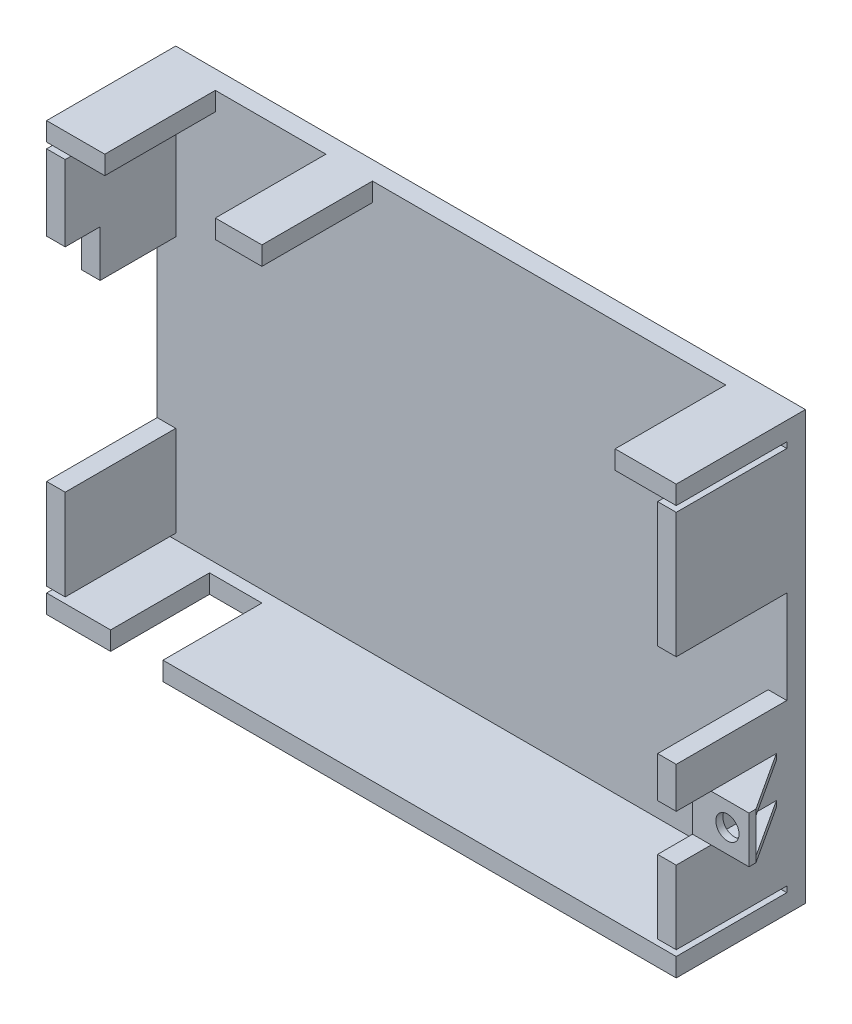
SolidWorks part; units mm, degrees
ref_plane "Front Plane" through (0, 0, 0) normal (0, 0, 1) x (1, 0, 0)
ref_plane "Top Plane" through (0, 0, 0) normal (0, 1, 0) x (1, 0, 0)
ref_plane "Right Plane" through (0, 0, 0) normal (1, 0, 0) x (0, 0, -1)
sketch "Sketch1" plane through (0, 0, 0) normal (0, 0, 1) x (1, 0, 0)
  line L1 (0, 0) -> (108.2, 0)
  line L2 (0, 0) -> (0, 73.5)
  line L3 (0, 73.5) -> (108.2, 73.5)
  line L4 (108.2, 0) -> (108.2, 73.5)
  dimension "D1" = 73.5
  dimension "D2" = 108.2
extrude "Boss-Extrude2" add sketch "Sketch1" along normal blind 3.2
sketch "Sketch2" plane through (0, 0, 3.2) normal (0, 0, 1) x (1, 0, 0)
  line L1 (3.2, 3.2) -> (105, 3.2)
  line L2 (3.2, 3.2) -> (3.2, 70.3)
  line L3 (3.2, 70.3) -> (105, 70.3)
  line L4 (0, 73.5) -> (0, 0)
  line L5 (0, 0) -> (108.2, 0)
  line L6 (108.2, 0) -> (108.2, 73.5)
  line L7 (108.2, 73.5) -> (0, 73.5)
  line L8 (0, 73.5) -> (0, 0)
  line L9 (0, 0) -> (108.2, 0)
  line L10 (108.2, 0) -> (108.2, 73.5)
  line L11 (108.2, 73.5) -> (0, 73.5)
  line L12 (105, 3.2) -> (105, 70.3)
  dimension "D2" = 3.2
  dimension "D3" = 3.2
  dimension "D4" = 3.2
  dimension "D5" = 3.2
  dimension "D1" = 0
extrude "Boss-Extrude3" add sketch "Sketch2" along normal blind 19
sketch "Sketch3" plane through (0, 0, 22.2) normal (0, 0, 1) x (1, 0, 0)
  line L0 (3.2, 70.3) -> (0, 70.3)
  line L1 (0, 70.3) -> (0, 69.3)
  line L2 (0, 69.3) -> (3.2, 69.3)
  line L3 (3.2, 70.3) -> (3.2, 3.2) construction
  line L4 (108.2, 73.5) -> (0, 73.5)
  line L5 (0, 73.5) -> (0, 0)
  line L6 (0, 0) -> (108.2, 0)
  line L7 (108.2, 0) -> (108.2, 73.5)
  line L9 (0, 70.3) -> (0, 69.3)
  line L11 (108.2, 3.2) -> (108.2, 4.2)
  line L12 (3.2, 69.3) -> (3.2, 70.3)
  line L13 (105, 70.3) -> (108.2, 70.3)
  line L14 (108.2, 70.3) -> (108.2, 69.3)
  line L15 (108.2, 69.3) -> (105, 69.3)
  line L16 (105, 3.2) -> (105, 70.3) construction
  line L17 (105, 69.3) -> (105, 70.3)
  line L18 (105, 3.2) -> (108.2, 3.2)
  line L19 (108.2, 3.2) -> (108.2, 4.2)
  line L20 (108.2, 4.2) -> (105, 4.2)
  line L21 (105, 4.2) -> (105, 3.2)
  line L22 (3.2, 3.2) -> (0, 3.2)
  line L23 (0, 3.2) -> (0, 4.2)
  line L24 (0, 4.2) -> (3.2, 4.2)
  line L25 (3.2, 4.2) -> (3.2, 3.2)
  line L26 (0, 4.2) -> (0, 0)
  line L27 (108.2, 69.3) -> (108.2, 70.3)
  line M10 (0, 73.5) -> (0, 0)
  line M12 (108.2, 0) -> (108.2, 73.5)
  line M14 (3.2, 3.2) -> (3.2, 70.3)
  line M16 (105, 70.3) -> (105, 3.2)
  dimension "D1" = 0
  dimension "D2" = 1
  dimension "D3" = 1
  dimension "D4" = 1
  dimension "D5" = 1
extrude "Cut-Extrude1" cut sketch "Sketch3" against normal blind 19 contours L2 L0 M10 M14 | L15 L13 M12 M16 | L20 L18 M12 M16 | L24 L25 L22 L23
sketch "Sketch4" plane through (0, 0, 22.2) normal (0, 0, 1) x (1, 0, 0)
  line L0 (0, 48.3) -> (3.2, 48.3)
  line L1 (0, 19.8) -> (3.2, 19.8)
  line L4 (0, 69.3) -> (0, 4.2)
  line L5 (0, 4.2) -> (3.2, 4.2)
  line L6 (3.2, 4.2) -> (3.2, 69.3)
  line L7 (3.2, 69.3) -> (0, 69.3)
  line L8 (0, 48.3) -> (0, 19.8)
  line L9 (0, 4.2) -> (3.2, 4.2) construction
  line L10 (3.2, 19.8) -> (3.2, 48.3)
  line L11 (3.2, 69.3) -> (0, 69.3) construction
  point P8 (1.6, 4.2)
  dimension "D2" = 21
  dimension "D3" = 15.6
  dimension "D1" = 0
extrude "Cut-Extrude2" cut sketch "Sketch4" against normal blind 19
sketch "Sketch5" plane through (0, 0, 22.2) normal (0, 0, 1) x (1, 0, 0)
  line L0 (10, 73.5) -> (10, 70.3)
  line L1 (29, 73.5) -> (29, 70.3)
  line L2 (37, 73.5) -> (37, 70.3)
  line L3 (97.7, 73.5) -> (97.7, 70.3)
  line L4 (0, 70.3) -> (108.2, 70.3)
  line L5 (108.2, 70.3) -> (108.2, 73.5)
  line L6 (108.2, 73.5) -> (0, 73.5)
  line L7 (0, 73.5) -> (0, 70.3)
  line L8 (10, 70.3) -> (29, 70.3)
  line L9 (108.2, 70.3) -> (108.2, 73.5) construction
  line L10 (97.7, 73.5) -> (37, 73.5)
  line L11 (0, 73.5) -> (0, 70.3) construction
  line L12 (29, 73.5) -> (10, 73.5)
  line L13 (37, 70.3) -> (97.7, 70.3)
  dimension "D2" = 10
  dimension "D3" = 19
  dimension "D4" = 8
  dimension "D5" = 10.5
  dimension "D1" = 0
extrude "Cut-Extrude3" cut sketch "Sketch5" against normal blind 19
sketch "Sketch6" plane through (0, 0, 22.2) normal (0, 0, 1) x (1, 0, 0)
  line L0 (105, 31.8) -> (108.2, 31.8)
  line L1 (105, 47.8) -> (108.2, 47.8)
  line L4 (105, 4.2) -> (108.2, 4.2)
  line L5 (108.2, 4.2) -> (108.2, 69.3)
  line L6 (108.2, 69.3) -> (105, 69.3)
  line L7 (105, 69.3) -> (105, 4.2)
  line L8 (105, 4.2) -> (108.2, 4.2) construction
  line L9 (108.2, 31.8) -> (108.2, 47.8)
  line L10 (108.2, 69.3) -> (105, 69.3) construction
  line L11 (105, 47.8) -> (105, 31.8)
  dimension "D2" = 21.5
  dimension "D3" = 16
  dimension "D1" = 0
extrude "Cut-Extrude4" cut sketch "Sketch6" against normal blind 19
sketch "Sketch7" plane through (0, 0, 22.2) normal (0, 0, 1) x (1, 0, 0)
  line L0 (11, 3.2) -> (11, 0)
  line L1 (20, 3.2) -> (20, 0)
  line L4 (108.2, 3.2) -> (0, 3.2)
  line L5 (0, 3.2) -> (0, 0)
  line L6 (0, 0) -> (108.2, 0)
  line L7 (108.2, 0) -> (108.2, 3.2)
  line L8 (20, 3.2) -> (11, 3.2)
  line L9 (0, 3.2) -> (0, 0) construction
  line L10 (11, 0) -> (20, 0)
  line L11 (108.2, 0) -> (108.2, 3.2) construction
  dimension "D2" = 11
  dimension "D3" = 9
  dimension "D1" = 0
extrude "Cut-Extrude5" cut sketch "Sketch7" against normal blind 17
sketch "Sketch8" plane through (0, 0, 0) normal (-1, 0, 0) x (0, 0, 1)
  line L1 (22.2, 48.3) -> (16.2, 48.3)
  line L2 (22.2, 48.3) -> (22.2, 56.3)
  line L3 (22.2, 56.3) -> (16.2, 56.3)
  line L4 (16.2, 48.3) -> (16.2, 56.3)
  dimension "D1" = 6
  dimension "D2" = 8
extrude "Cut-Extrude6" cut sketch "Sketch8" against normal up to next
sketch "Sketch9" plane through (108.2, 0, 0) normal (1, 0, 0) x (0, 0, -1)
  line L0 (-22.2, 4.2) -> (-22.2, 31.8) construction
  line L1 (-22.2, 16.8) -> (-16.2, 16.8)
  line L2 (-22.2, 16.8) -> (-22.2, 24.8)
  line L3 (-22.2, 24.8) -> (-16.2, 24.8)
  line L4 (-16.2, 16.8) -> (-16.2, 24.8)
  line L5 (-3.2, 31.8) -> (-22.2, 31.8) construction
  dimension "D1" = 6
  dimension "D2" = 7
  dimension "D3" = 8
extrude "Cut-Extrude7" cut sketch "Sketch9" against normal up to next
sketch "Sketch10" plane through (108.2, 0, 0) normal (1, 0, 0) x (0, 0, -1)
  line L0 (-16.2, 16.8) -> (-16.2, 24.8)
  line L1 (-16.2, 24.8) -> (-15, 24.8)
  line L2 (-15, 24.8) -> (-15, 16.8)
  line L3 (-15, 16.8) -> (-16.2, 16.8)
  dimension "D1" = 1.2
extrude "Boss-Extrude4" add sketch "Sketch10" along normal blind 6.5
sketch "Sketch11" plane through (0, 0, 15) normal (0, 0, -1) x (-1, 0, 0)
  line L0 (-114.7, 20.8) -> (-108.2, 20.8) construction
  line L1 (-114.7, 16.8) -> (-114.7, 24.8) construction
  line L2 (-108.2, 16.8) -> (-108.2, 24.8) construction
  circle A0 centre (-111, 20.8) radius 2
  dimension "D1" = 4
  dimension "D2" = 2.8
extrude "Cut-Extrude8" cut sketch "Sketch11" against normal up to next
sketch "Sketch12" plane through (0, 0, 15) normal (0, 0, -1) x (-1, 0, 0)
  line L0 (-108.2, 16.8) -> (-108.2, 24.8) construction
  line L1 (-114.7, 24.8) -> (-108.2, 24.8)
  line L2 (-114.7, 24.8) -> (-114.7, 23.8)
  line L3 (-114.7, 23.8) -> (-108.2, 23.8)
  line L4 (-108.2, 24.8) -> (-108.2, 23.8)
  line L6 (-114.7, 16.8) -> (-108.2, 16.8)
  line L7 (-114.7, 16.8) -> (-114.7, 17.8)
  line L8 (-114.7, 17.8) -> (-108.2, 17.8)
  line L9 (-108.2, 16.8) -> (-108.2, 17.8)
  dimension "D1" = 1
  dimension "D2" = 1
extrude "Boss-Extrude5" add sketch "Sketch12" along normal blind 10
chamfer "Chamfer1" distance 10 angle 33 2 edges at (114.7, 17.3, 5) (114.7, 24.3, 5)
equation "\"WallThickness\"= 3.2mm"
equation "\"D2@Sketch2\"=\"WallThickness\""
equation "\"D3@Sketch2\"=\"WallThickness\""
equation "\"D4@Sketch2\"=\"WallThickness\""
equation "\"D5@Sketch2\"=\"WallThickness\""
equation "\"CornerBreakDist\"= 1mm"
equation "\"D2@Sketch3\"=\"CornerBreakDist\""
equation "\"D3@Sketch3\"=\"CornerBreakDist\""
equation "\"D4@Sketch3\"=\"CornerBreakDist\""
equation "\"D5@Sketch3\"=\"CornerBreakDist\""
